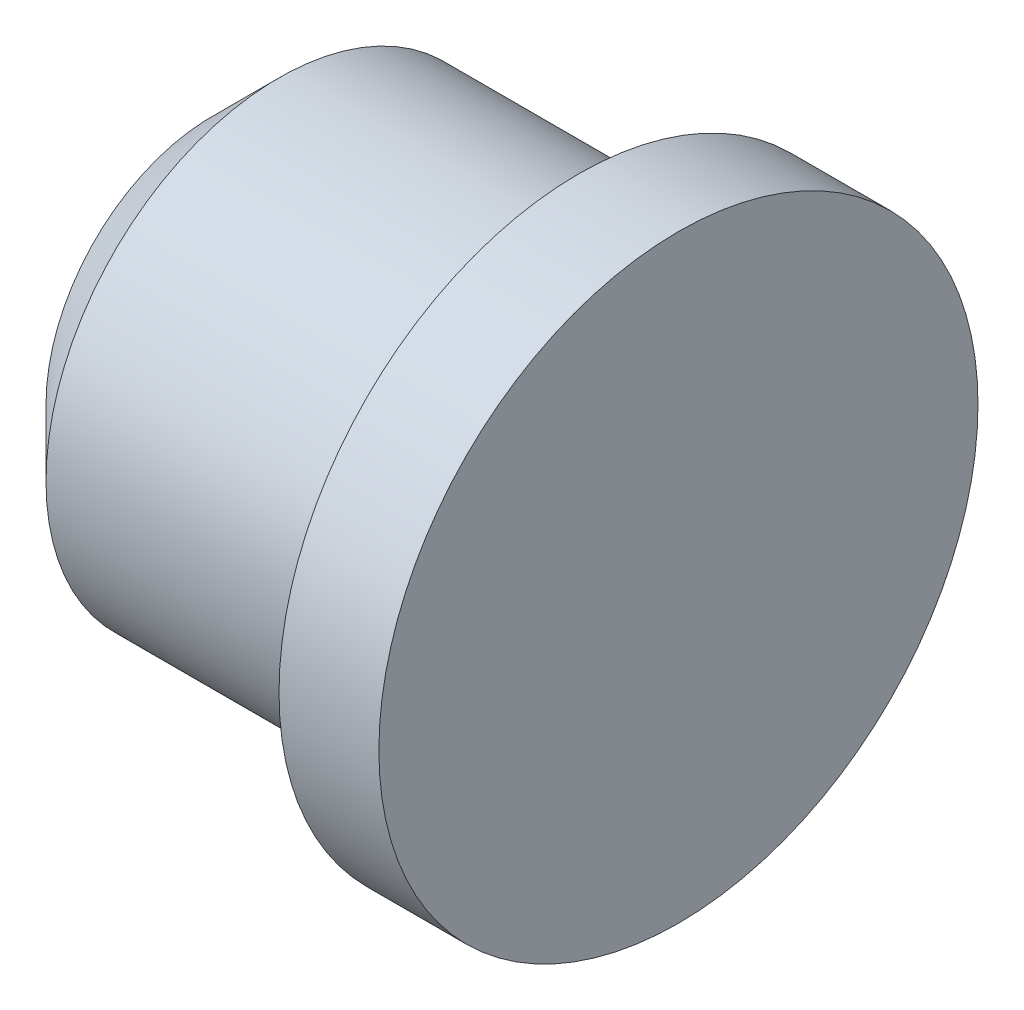
SolidWorks part; units mm, degrees
ref_plane "XZ (Face)" through (0, 0, 0) normal (0, 0, 1) x (1, 0, 0)
ref_plane "XY (Dessus)" through (0, 0, 0) normal (0, 1, 0) x (1, 0, 0)
ref_plane "YZ (Droite)" through (0, 0, 0) normal (1, 0, 0) x (0, 0, -1)
sketch "Esquisse1" plane through (0, 0, 0) normal (0, 0, 1) x (1, 0, 0)
  line L0 (8, 10.75) -> (5.25, 10.75)
  line L1 (8, 10.75) -> (-8, 10.75) construction
  line L2 (8.75, 11.25) -> (8, 11.25)
  line L3 (9.5, 11.25) -> (7, 11.25) construction
  line L4 (8, 11.25) -> (-8, 11.25) construction
  line L5 (8.75, 11.25) -> (8.75, 9)
  line L6 (11, 9) -> (-12, 9) construction
  line L7 (-6.6285, 9) -> (-9.2297, 9) construction
  line L8 (8, 11.25) -> (8, 10.75)
  line L9 (8, 6.75) -> (8, 11.25) construction
  line L10 (5.25, 10.75) -> (5.25, 9)
  line L11 (5.25, 9) -> (8.75, 9)
  dimension "D1" = 0.75
  dimension "D2" = 3.5
revolve "Base-Révolution" add sketch "Esquisse1" angle 360 about L6
chamfer "Chanfrein1" distance 0.5 angle 45
